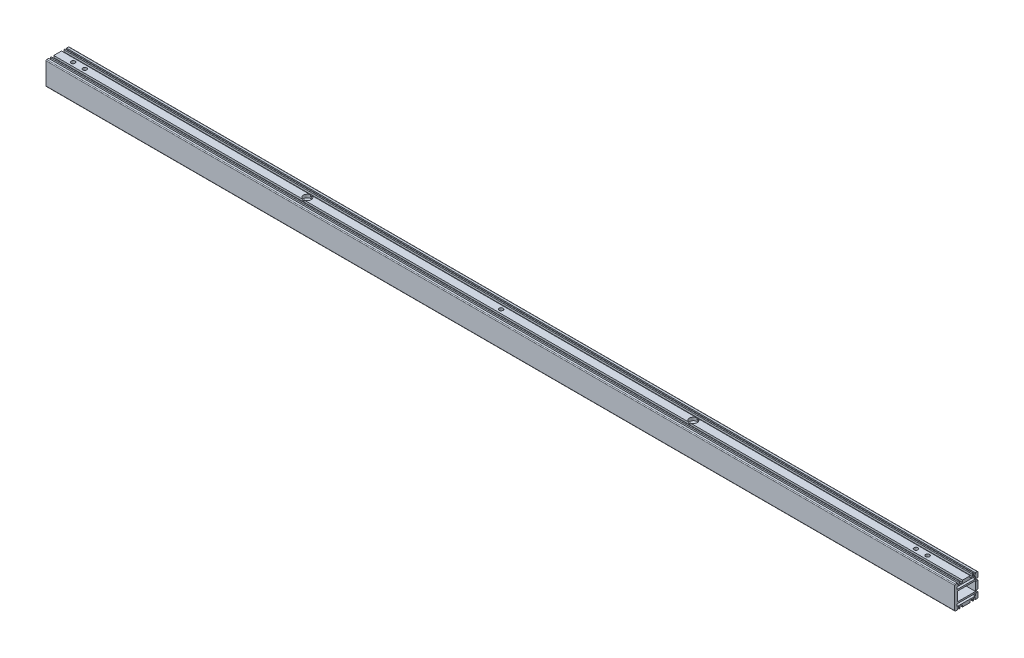
SolidWorks part; units mm, degrees
ref_plane "前视基准面" through (0, 0, 0) normal (0, 0, 1) x (1, 0, 0)
ref_plane "上视基准面" through (0, 0, 0) normal (0, 1, 0) x (1, 0, 0)
ref_plane "右视基准面" through (0, 0, 0) normal (1, 0, 0) x (0, 0, -1)
sketch "草图1" plane through (0, 0, 0) normal (1, 0, 0) x (0, 0, -1)
  line L0 (-15, 15) -> (15, -15) construction
  line L1 (-14, 15) -> (-11.5, 15)
  line L2 (-15, 14) -> (-15, -14)
  line L3 (-14, -15) -> (-11.5, -15)
  line L4 (15, 14) -> (15, 8)
  line L5 (15, 15) -> (-15, -15) construction
  line L6 (-11.5, 15) -> (-11.5, 13.5)
  line L7 (-11.5, 13.5) -> (-11.4, 13.5)
  line L8 (-11, 13.1) -> (-11, 12)
  line L9 (-11, 12) -> (-9.5, 12)
  line L10 (-9.5, 12) -> (-9.5, 15)
  line L11 (-9.5, 15) -> (-8, 15)
  line L12 (-8, 15) -> (-8, 12.5)
  line L13 (-8, 12.5) -> (-5, 12.5)
  line L14 (-5, 12.5) -> (-5, 15)
  line L15 (-5, 15) -> (5, 15)
  line L16 (0, 21.5201) -> (0, -18.309) construction
  line L17 (0, 55) -> (0, -55) construction
  line L18 (5, 12.5) -> (5, 15)
  line L19 (8, 12.5) -> (5, 12.5)
  line L20 (8, 15) -> (8, 12.5)
  line L21 (9.5, 15) -> (8, 15)
  line L22 (9.5, 12) -> (9.5, 15)
  line L23 (11, 12) -> (9.5, 12)
  line L24 (11, 13.1) -> (11, 12)
  line L25 (11.5, 13.5) -> (11.4, 13.5)
  line L26 (11.5, 15) -> (11.5, 13.5)
  line L27 (8, 15) -> (9.5, 15)
  line L28 (11.5, 15) -> (14, 15)
  line L29 (-19.8303, 0) -> (22.13, 0) construction
  line L30 (55, 0) -> (-55, 0) construction
  line L31 (8, -15) -> (9.5, -15)
  line L32 (11.5, -15) -> (11.5, -13.5)
  line L33 (11.5, -13.5) -> (11.4, -13.5)
  line L34 (11, -13.1) -> (11, -12)
  line L35 (11, -12) -> (9.5, -12)
  line L36 (9.5, -12) -> (9.5, -15)
  line L37 (9.5, -15) -> (8, -15)
  line L38 (8, -15) -> (8, -12.5)
  line L39 (8, -12.5) -> (5, -12.5)
  line L40 (5, -12.5) -> (5, -15)
  line L41 (-5, -15) -> (5, -15)
  line L42 (-5, -12.5) -> (-5, -15)
  line L43 (-8, -12.5) -> (-5, -12.5)
  line L44 (-8, -15) -> (-8, -12.5)
  line L45 (-9.5, -15) -> (-8, -15)
  line L46 (-9.5, -12) -> (-9.5, -15)
  line L47 (-11, -12) -> (-9.5, -12)
  line L48 (-11, -13.1) -> (-11, -12)
  line L49 (-11.5, -13.5) -> (-11.4, -13.5)
  line L50 (-11.5, -15) -> (-11.5, -13.5)
  line L51 (-9.5, -15) -> (-8, -15)
  line L52 (-5, -15) -> (5, -15)
  line L53 (8, -15) -> (9.5, -15)
  line L54 (11.5, -15) -> (14, -15)
  line L55 (15, 8) -> (12.5, 8)
  line L56 (12.5, 8) -> (12.5, 5)
  line L57 (12.5, 5) -> (15, 5)
  line L58 (12.5, -5) -> (15, -5)
  line L59 (12.5, -8) -> (12.5, -5)
  line L60 (15, -8) -> (12.5, -8)
  line L61 (15, 5) -> (15, -5)
  line L62 (15, -8) -> (15, -14)
  line L63 (12, -10.5) -> (12, -8.5)
  line L64 (-11.5, 11) -> (11.5, 11)
  line L65 (-12, 10.5) -> (-12, 8.5)
  line L66 (-11.5, 8) -> (11.5, 8)
  line L67 (12, 10.5) -> (12, 8.5)
  line L68 (-11.5, -8) -> (11.5, -8)
  line L69 (-12, -10.5) -> (-12, -8.5)
  line L70 (-11.5, -11) -> (11.5, -11)
  line L72 (-11.75, 6) -> (11.75, 6)
  line L73 (-11.75, 6) -> (-11.75, -6)
  line L74 (-11.75, -6) -> (11.75, -6)
  line L75 (11.75, 6) -> (11.75, -6)
  arc A0 (12, 8.5) -> (11.5, 8) centre (11.5, 8.5) cw
  arc A1 (11.5, 11) -> (12, 10.5) centre (11.5, 10.5) cw
  arc A2 (-11.5, 11) -> (-12, 10.5) centre (-11.5, 10.5) ccw
  arc A3 (-11.5, 8) -> (-12, 8.5) centre (-11.5, 8.5) cw
  arc A4 (-11, -13.1) -> (-11.4, -13.5) centre (-11.4, -13.1) cw
  arc A5 (11.4, -13.5) -> (11, -13.1) centre (11.4, -13.1) cw
  arc A6 (11.4, 13.5) -> (11, 13.1) centre (11.4, 13.1) ccw
  arc A7 (-11, 13.1) -> (-11.4, 13.5) centre (-11.4, 13.1) ccw
  arc A8 (-11.5, -8) -> (-12, -8.5) centre (-11.5, -8.5) ccw
  arc A9 (-11.5, -11) -> (-12, -10.5) centre (-11.5, -10.5) cw
  arc A10 (11.5, -11) -> (12, -10.5) centre (11.5, -10.5) ccw
  arc A11 (12, -8.5) -> (11.5, -8) centre (11.5, -8.5) ccw
  arc A12 (14, 15) -> (15, 14) centre (14, 14) cw
  arc A13 (14, -15) -> (15, -14) centre (14, -14) ccw
  arc A14 (-15, -14) -> (-14, -15) centre (-14, -14) ccw
  arc A15 (-15, 14) -> (-14, 15) centre (-14, 14) cw
  point P69 (12, 11)
  point P72 (-12, 11)
  point P77 (-11, -13.5)
  point P80 (11, -13.5)
  point P83 (11, 13.5)
  point P86 (-11, 13.5)
  point P99 (-12, -11)
  point P100 (12, -11)
  dimension "D17" = 0.5
  dimension "D18" = 0.4
  dimension "D21" = 1
  dimension "D1" = 3.5
  dimension "D2" = 1.5
  dimension "D3" = 0.5
  dimension "D4" = 1.5
  dimension "D5" = 3
  dimension "D6" = 30
  dimension "D7" = 30
  dimension "D8" = 1.5
  dimension "D9" = 2.5
  dimension "D10" = 3
  dimension "D11" = 2.5
  dimension "D12" = 7
  dimension "D13" = 3
  dimension "D14" = 4
  dimension "D15" = 3
  dimension "D16" = 24
  dimension "D19" = 23.5
  dimension "D20" = 12
extrude "凸台-拉伸1" add sketch "草图1" along normal mid plane 1172 contours A15 L2 A14 L3 L50 L49 A4 L48 L47 L46 L45 L44 L43 L42 L41 L40 L39 L38 L31 L36 L35 L34 A5 L33 L32 L54 A13 L62 L60 L59 L58 L61 L57 L56 L55 L4 A12 L28 L26 L25 A6 L24 L23 L22 L21 L20 L19 L18 L15 L14 L13
hole_wizard "M6 螺纹孔1" positions "草图3" profile "草图2" tap size "M6" standard "GB"
sketch "草图3" plane through (0, -15, 0) normal (0, -1, 0) x (1, 0, 0)
  line L0 (-586, 5) -> (-586, -5) construction
  line L1 (586, 15) -> (-586, 15) construction
  point P0 (-566, 0)
  point P1 (-551, 0)
  point P4 (184, 0)
  point P7 (199, 0)
  dimension "D1" = 20
  dimension "D2" = 15
sketch "草图2" plane through (-566, -15, 0) normal (1, 0, 0) x (0, 0, -1)
  line L0 (0, 0) -> (0, 16.5022)
  line L1 (0, 16.5022) -> (2.5, 15)
  line L2 (2.5, 15) -> (2.5, 0)
  line L5 (2.5, 0) -> (0, 0)
  line L10 (0, 16.5022) -> (-2.5, 15) construction
  line L11 (0, -6.35) -> (0, 107.95) construction
  dimension "螺纹孔钻头直径" = 5
  dimension "螺纹孔钻头深度" = 15
  dimension "导头角度" = 118
cosmetic thread "孔螺蚊线1" parameters "D1"=9, "D2"=6
cosmetic thread "孔螺蚊线2" parameters "D1"=9, "D2"=6
cosmetic thread "孔螺蚊线3" parameters "D1"=9, "D2"=6
cosmetic thread "孔螺蚊线4" parameters "D1"=9, "D2"=6
hole_wizard "M6 螺纹孔2" positions "草图5" profile "草图4" tap size "M6" standard "GB"
sketch "草图5" plane through (0, 0, -15) normal (0, 0, -1) x (-1, 0, 0)
  line L0 (586, 5) -> (586, -5) construction
  line L1 (-586, -15) -> (586, -15) construction
  line L2 (-586, 5) -> (-586, -5) construction
  point P0 (566, 0)
  point P1 (551, 0)
  point P4 (-521, 0)
  point P7 (-536, 0)
  point P15 (-448, 0)
  point P17 (-361, 0)
  point P19 (-344, 0)
  dimension "D1" = 20
  dimension "D2" = 15
  dimension "D3" = 138
  dimension "D4" = 104
  dimension "D5" = 225
sketch "草图4" plane through (-566, 0, -15) normal (1, 0, 0) x (0, 1, 0)
  line L0 (0, 0) -> (0, 16.5022)
  line L1 (0, 16.5022) -> (2.5, 15)
  line L2 (2.5, 15) -> (2.5, 0)
  line L5 (2.5, 0) -> (0, 0)
  line L10 (0, 16.5022) -> (-2.5, 15) construction
  line L11 (0, -6.35) -> (0, 107.95) construction
  dimension "螺纹孔钻头直径" = 5
  dimension "螺纹孔钻头深度" = 15
  dimension "导头角度" = 118
cosmetic thread "孔螺蚊线5" parameters "D1"=3.25, "D2"=6
cosmetic thread "孔螺蚊线6" parameters "D1"=3.25, "D2"=6
cosmetic thread "孔螺蚊线7" parameters "D1"=3.25, "D2"=6
cosmetic thread "孔螺蚊线8" parameters "D1"=3.25, "D2"=6
cosmetic thread "孔螺蚊线26" parameters "D1"=3.25, "D2"=6
cosmetic thread "孔螺蚊线27" parameters "D1"=3.25, "D2"=6
cosmetic thread "孔螺蚊线28" parameters "D1"=3.25, "D2"=6
hole_wizard "M6 螺纹孔3" positions "草图9" profile "草图8" tap size "M6" standard "GB"
sketch "草图9" plane through (0, 15, 0) normal (0, 1, 0) x (-1, 0, 0)
  line L0 (-556, 5) -> (-556, -5) construction
  line L1 (-586, 15) -> (586, 15) construction
  line L2 (586, 5) -> (586, -5) construction
  line L3 (-586, -15) -> (586, -15) construction
  point P0 (-536, 0)
  point P1 (-521, 0)
  point P4 (551, 0)
  point P7 (566, 0)
  point P17 (14, 0)
  dimension "D1" = 20
  dimension "D2" = 15
  dimension "D3" = 572
  dimension "D4" = 15
sketch "草图8" plane through (536, 15, 0) normal (1, 0, 0) x (0, 0, 1)
  line L0 (0, 0) -> (0, 16.5022)
  line L1 (0, 16.5022) -> (2.5, 15)
  line L2 (2.5, 15) -> (2.5, 0)
  line L5 (2.5, 0) -> (0, 0)
  line L10 (0, 16.5022) -> (-2.5, 15) construction
  line L11 (0, -6.35) -> (0, 107.95) construction
  dimension "螺纹孔钻头直径" = 5
  dimension "螺纹孔钻头深度" = 15
  dimension "导头角度" = 118
cosmetic thread "孔螺蚊线9" parameters "D1"=9, "D2"=6
cosmetic thread "孔螺蚊线10" parameters "D1"=9, "D2"=6
cosmetic thread "孔螺蚊线11" parameters "D1"=9, "D2"=6
cosmetic thread "孔螺蚊线12" parameters "D1"=9, "D2"=6
cosmetic thread "孔螺蚊线29" parameters "D1"=9, "D2"=6
sketch "草图10" plane through (0, 15, 0) normal (0, 1, 0) x (1, 0, 0)
  line L0 (586, -15) -> (-586, -15) construction
  line L1 (586, -5) -> (586, 5) construction
  line L2 (-586, -5) -> (-586, 5) construction
  circle A0 centre (234, 0) radius 5.05
  circle A1 centre (-264, 0) radius 5.05
  dimension "D1" = 10.1
  dimension "D2" = 15
  dimension "D3" = 352
  dimension "D4" = 15
  dimension "D5" = 322
extrude "切除-拉伸1" cut sketch "草图10" against normal through all
hole_wizard "M4 螺纹孔1" positions "草图12" profile "草图11" tap size "M4" standard "GB"
sketch "草图12" plane through (0, -15, 0) normal (0, -1, 0) x (1, 0, 0)
  line L0 (586, -15) -> (-586, -15) construction
  line L1 (586, 5) -> (586, -5) construction
  point P0 (137, 0)
  point P1 (-23, 0)
  point P3 (-183, 0)
  point P5 (-343, 0)
  point P7 (-503, 0)
  dimension "D1" = 15
  dimension "D2" = 449
  dimension "D3" = 160
  dimension "D4" = 160
  dimension "D5" = 160
  dimension "D6" = 160
sketch "草图11" plane through (137, -15, 0) normal (1, 0, 0) x (0, 0, -1)
  line L0 (0, 0) -> (0, 11.0914)
  line L1 (0, 11.0914) -> (1.65, 10.1)
  line L2 (1.65, 10.1) -> (1.65, 0)
  line L5 (1.65, 0) -> (0, 0)
  line L10 (0, 11.0914) -> (-1.65, 10.1) construction
  line L11 (0, -6.35) -> (0, 107.95) construction
  dimension "螺纹孔钻头直径" = 3.3
  dimension "螺纹孔钻头深度" = 10.1
  dimension "导头角度" = 118
cosmetic thread "孔螺蚊线13" parameters "D1"=8, "D2"=4
cosmetic thread "孔螺蚊线14" parameters "D1"=8, "D2"=4
cosmetic thread "孔螺蚊线15" parameters "D1"=8, "D2"=4
cosmetic thread "孔螺蚊线16" parameters "D1"=8, "D2"=4
cosmetic thread "孔螺蚊线17" parameters "D1"=8, "D2"=4
hole_wizard "M4 螺纹孔2" positions "草图16" profile "草图15" tap size "M4" standard "GB"
sketch "草图16" plane through (0, -15, 0) normal (0, -1, 0) x (1, 0, 0)
  line L0 (586, 5) -> (586, -5) construction
  line L1 (586, 15) -> (-586, 15) construction
  point P1 (461, 0)
  point P3 (261, 0)
  dimension "D1" = 125
  dimension "D2" = 200
  dimension "D3" = 15
  dimension "D4" = 15
sketch "草图15" plane through (461, -15, 0) normal (1, 0, 0) x (0, 0, -1)
  line L0 (0, 0) -> (0, 11.0914)
  line L1 (0, 11.0914) -> (1.65, 10.1)
  line L2 (1.65, 10.1) -> (1.65, 0)
  line L5 (1.65, 0) -> (0, 0)
  line L10 (0, 11.0914) -> (-1.65, 10.1) construction
  line L11 (0, -6.35) -> (0, 107.95) construction
  dimension "螺纹孔钻头直径" = 3.3
  dimension "螺纹孔钻头深度" = 10.1
  dimension "导头角度" = 118
cosmetic thread "孔螺蚊线18" parameters "D1"=8, "D2"=4
cosmetic thread "孔螺蚊线19" parameters "D1"=8, "D2"=4
hole_wizard "M4 螺纹孔3" positions "草图18" profile "草图17" tap size "M4" standard "GB"
sketch "草图18" plane through (0, -15, 0) normal (0, -1, 0) x (1, 0, 0)
  line L0 (586, 5) -> (586, -5) construction
  line L1 (586, 15) -> (-586, 15) construction
  point P1 (571, 0)
  point P3 (496, 0)
  dimension "D1" = 15
  dimension "D2" = 75
  dimension "D3" = 15
  dimension "D4" = 15
sketch "草图17" plane through (571, -15, 0) normal (1, 0, 0) x (0, 0, -1)
  line L0 (0, 0) -> (0, 11.0914)
  line L1 (0, 11.0914) -> (1.65, 10.1)
  line L2 (1.65, 10.1) -> (1.65, 0)
  line L5 (1.65, 0) -> (0, 0)
  line L10 (0, 11.0914) -> (-1.65, 10.1) construction
  line L11 (0, -6.35) -> (0, 107.95) construction
  dimension "螺纹孔钻头直径" = 3.3
  dimension "螺纹孔钻头深度" = 10.1
  dimension "导头角度" = 118
cosmetic thread "孔螺蚊线20" parameters "D1"=8, "D2"=4
cosmetic thread "孔螺蚊线21" parameters "D1"=8, "D2"=4
hole_wizard "M6 螺纹孔4" positions "草图20" profile "草图19" tap size "M6" standard "GB"
sketch "草图20" plane through (0, 0, -15) normal (0, 0, -1) x (-1, 0, 0)
  line L0 (-233.2911, 15) -> (263.2911, 15) construction
  line L1 (586, 14) -> (586, 8) construction
  line L2 (-586, 5) -> (-586, -5) construction
  point P0 (-326, 0)
  point P1 (-266, 0)
  point P3 (296, 0)
  point P5 (356, 0)
  dimension "D1" = 60
  dimension "D2" = 15
  dimension "D3" = 230
  dimension "D4" = 60
  dimension "D5" = 260
sketch "草图19" plane through (326, 0, -15) normal (1, 0, 0) x (0, 1, 0)
  line L0 (0, 0) -> (0, 16.5022)
  line L1 (0, 16.5022) -> (2.5, 15)
  line L2 (2.5, 15) -> (2.5, 0)
  line L5 (2.5, 0) -> (0, 0)
  line L10 (0, 16.5022) -> (-2.5, 15) construction
  line L11 (0, -6.35) -> (0, 107.95) construction
  dimension "螺纹孔钻头直径" = 5
  dimension "螺纹孔钻头深度" = 15
  dimension "导头角度" = 118
cosmetic thread "孔螺蚊线22" parameters "D1"=3.25, "D2"=6
cosmetic thread "孔螺蚊线23" parameters "D1"=3.25, "D2"=6
cosmetic thread "孔螺蚊线24" parameters "D1"=3.25, "D2"=6
cosmetic thread "孔螺蚊线25" parameters "D1"=3.25, "D2"=6
